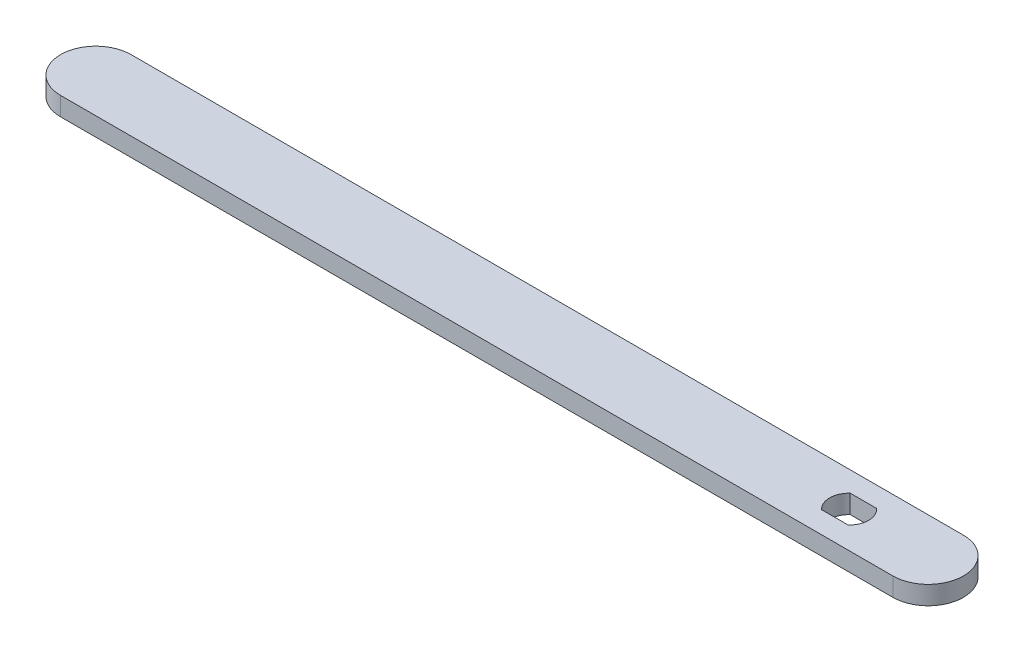
SolidWorks part; units mm, degrees
ref_plane "Front Plane" through (0, 0, 0) normal (0, 0, 1) x (1, 0, 0)
ref_plane "Top Plane" through (0, 0, 0) normal (0, 1, 0) x (1, 0, 0)
ref_plane "Right Plane" through (0, 0, 0) normal (1, 0, 0) x (0, 0, -1)
sketch "Sketch1" plane through (0, 0, 0) normal (0, 1, 0) x (1, 0, 0)
  line L0 (-11.5301, 0) -> (100.4699, 0) construction
  line L1 (-11.5301, 4.75) -> (100.4699, 4.75)
  line L2 (-11.5301, -4.75) -> (100.4699, -4.75)
  arc A0 (-11.5301, 4.75) -> (-11.5301, -4.75) centre (-11.5301, 0) ccw
  arc A1 (100.4699, -4.75) -> (100.4699, 4.75) centre (100.4699, 0) ccw
  point P3 (44.4699, 0)
  dimension "D2" = 112
  dimension "D1" = 9.5
extrude "Boss-Extrude1" add sketch "Sketch1" along normal blind 2.5 contours L1 A1 L2 A0
sketch "Sketch2" plane through (0, 2.5, 0) normal (0, 1, 0) x (1, 0, 0)
  line L3 (87.9545, 2.0253) -> (91.5238, 2.0253)
  line L5 (87.9545, -1.8247) -> (91.5238, -1.8247)
  line L7 (87.294, 1.0552) -> (92.1843, -0.8546) construction
  line L8 (87.294, -0.8546) -> (92.1843, 1.0552) construction
  arc A2 (87.9545, 2.0253) -> (87.9545, -1.8247) centre (89.7391, 0.1003) ccw
  arc A3 (91.5238, -1.8247) -> (91.5238, 2.0253) centre (89.7391, 0.1003) ccw
  dimension "D1" = 5.25
extrude "Cut-Extrude1" cut sketch "Sketch2" against normal through all both and the other way through all
